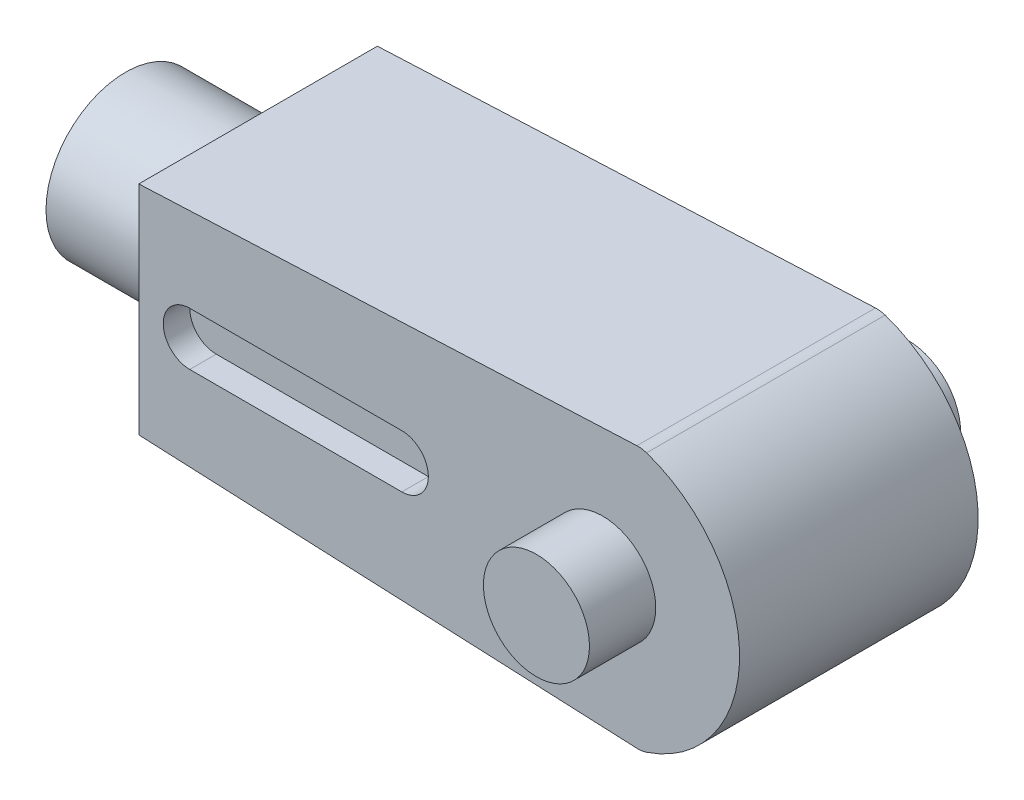
SolidWorks part; units mm, degrees
material "AISI 1020"
ref_plane "Front Plane" through (0, 0, 0) normal (0, 0, 1) x (1, 0, 0)
ref_plane "Top Plane" through (0, 0, 0) normal (0, 1, 0) x (1, 0, 0)
ref_plane "Right Plane" through (0, 0, 0) normal (1, 0, 0) x (0, 0, -1)
sketch "Sketch2" plane through (0, 0, 0) normal (0, 0, 1) x (1, 0, 0)
  line L0 (-80.9859, 41) -> (-80.9859, -41)
  line L2 (-80.9859, 41) -> (106.906, 49.4243)
  line L3 (-80.9859, -41) -> (106.906, -49.4243)
  circle A0 centre (94.0141, 0) radius 20
  arc A2 (110.5583, -48.907) -> (110.5583, 48.907) centre (94.0141, 0) ccw
  arc A3 (110.5583, -48.907) -> (106.906, -49.4243) centre (107.3539, -39.4343) cw
  arc A4 (110.5583, 48.907) -> (106.906, 49.4243) centre (107.3539, 39.4343) ccw
  point P2 (-80.9859, 0)
  dimension "D3" = 40
  dimension "D4" = 10
  dimension "D1" = 82
  dimension "D2" = 175
extrude "Boss-Extrude1" add sketch "Sketch2" along normal mid plane 90
sketch "Sketch3" plane through (-80.9859, 0, 0) normal (-1, 0, 0) x (0, 0, 1)
  circle A0 centre (0, 0) radius 30
  dimension "D1" = 60
extrude "Boss-Extrude2" add sketch "Sketch3" along normal blind 50
sketch "Sketch4" plane through (0, 0, 45) normal (0, 0, 1) x (1, 0, 0)
  circle A0 centre (94.0141, 0) radius 20 construction
  circle A1 centre (94.0141, 0) radius 20
extrude "Boss-Extrude3" add sketch "Sketch4" against normal blind 115 and the other way blind 25
sketch "Sketch5" plane through (0, 0, 45) normal (0, 0, 1) x (1, 0, 0)
  line L0 (-61.7583, 0) -> (18.2417, 0) construction
  line L1 (-61.7583, 10) -> (18.2417, 10)
  line L2 (-61.7583, -10) -> (18.2417, -10)
  line L3 (-80.9859, 41) -> (-80.9859, -41) construction
  arc A0 (-61.7583, 10) -> (-61.7583, -10) centre (-61.7583, 0) ccw
  arc A1 (18.2417, -10) -> (18.2417, 10) centre (18.2417, 0) ccw
  point P3 (-21.7583, 0)
  dimension "D1" = 10
  dimension "D2" = 80
  dimension "D3" = 19.2276
extrude "Cut-Extrude1" cut sketch "Sketch5" against normal blind 10
mirror "Mirror1" about plane through (0, 0, 0) normal (0, 0, 1) of "Cut-Extrude1"
